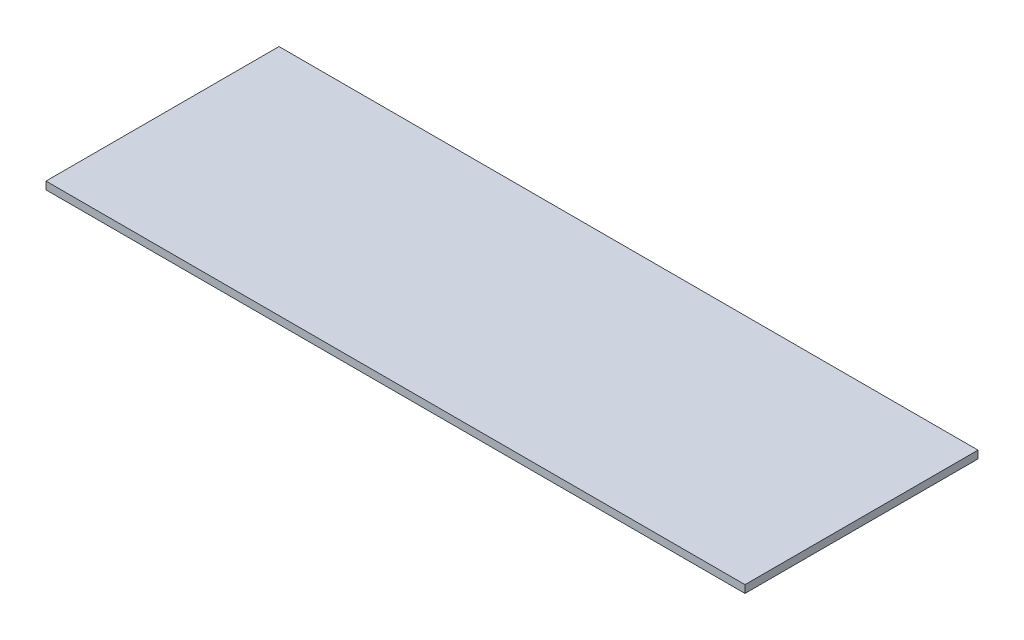
SolidWorks part; units mm, degrees
ref_plane "Front Plane" through (0, 0, 0) normal (0, 0, 1) x (1, 0, 0)
ref_plane "Top Plane" through (0, 0, 0) normal (0, 1, 0) x (1, 0, 0)
ref_plane "Right Plane" through (0, 0, 0) normal (1, 0, 0) x (0, 0, -1)
sketch "Sketch1" plane through (0, 0, 0) normal (0, 1, 0) x (1, 0, 0)
  line L1 (-457.2, 152.4) -> (457.2, 152.4)
  line L2 (-457.2, 152.4) -> (-457.2, -152.4)
  line L3 (-457.2, -152.4) -> (457.2, -152.4)
  line L4 (457.2, 152.4) -> (457.2, -152.4)
  line L5 (-457.2, 152.4) -> (457.2, -152.4) construction
  line L6 (-457.2, -152.4) -> (457.2, 152.4) construction
  point P0 (0, 0)
  dimension "D1" = 304.8
  dimension "D2" = 914.4
extrude "Boss-Extrude1" add sketch "Sketch1" along normal blind 10
